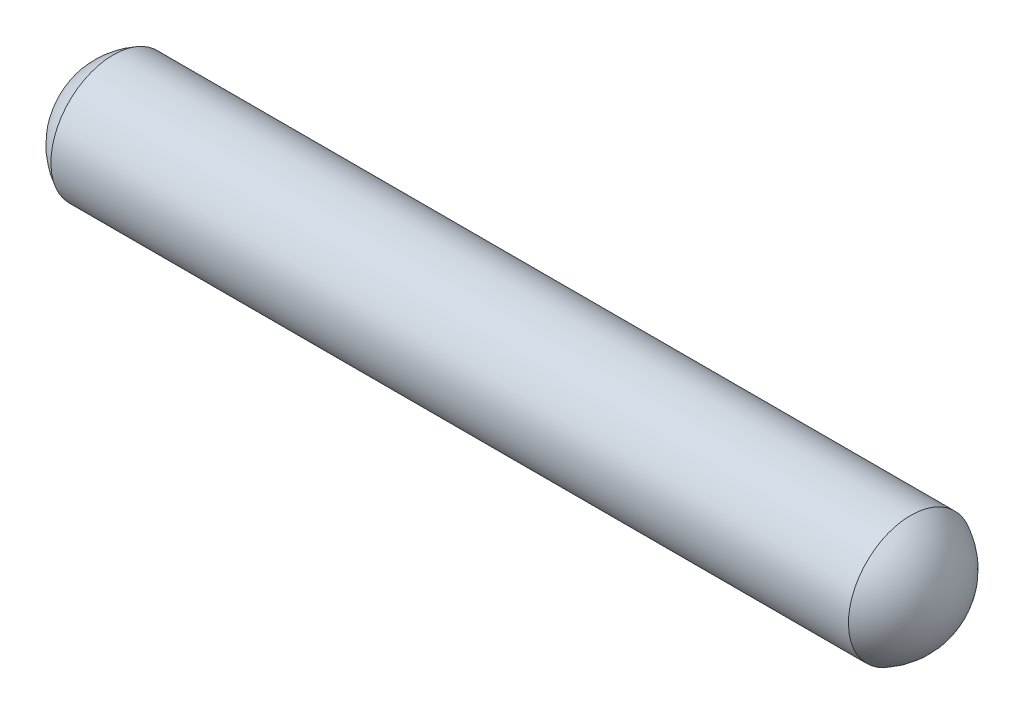
SolidWorks part; units mm, degrees
ref_plane "Plan de face" through (0, 0, 0) normal (0, 0, 1) x (1, 0, 0)
ref_plane "Plan de dessus" through (0, 0, 0) normal (0, 1, 0) x (1, 0, 0)
ref_plane "Plan de droite" through (0, 0, 0) normal (1, 0, 0) x (0, 0, -1)
sketch "Esquisse1" plane through (0, 0, 0) normal (0, 0, 1) x (1, 0, 0)
  line L1 (-16, 2.5) -> (0, 2.5)
  line L2 (0, 2.5) -> (0, 0)
  line L3 (0, 0) -> (-17.5451, 0)
  line L4 (-17.5451, 0) -> (-17.5451, 3.4839) construction
  arc A0 (-16, 2.5) -> (-17.5451, 0) centre (-14.75, 0) ccw
  point P6 (0, 0)
  dimension "D3" = 16
  dimension "D1" = 1.25
  dimension "D2" = 2.5
revolve "Révolution1" add sketch "Esquisse1" angle 360 about L3
mirror "Symétrie2" about plane through (0, 2.5, 0) normal (1, 0, 0) of "Révolution1"
